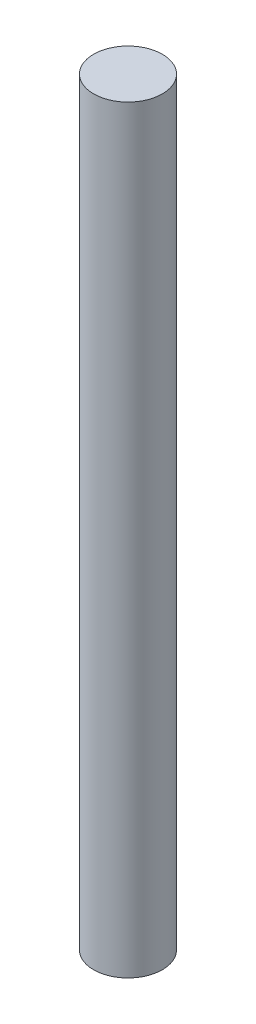
SolidWorks part; units mm, degrees
ref_plane "Front Plane" through (0, 0, 0) normal (0, 0, 1) x (1, 0, 0)
ref_plane "Top Plane" through (0, 0, 0) normal (0, 1, 0) x (1, 0, 0)
ref_plane "Right Plane" through (0, 0, 0) normal (1, 0, 0) x (0, 0, -1)
sketch "Sketch1" plane through (0, 0, 0) normal (0, 1, 0) x (1, 0, 0)
  circle A0 centre (0, 0) radius 6.477
  dimension "D1" = 12.954
extrude "Boss-Extrude1" add sketch "Sketch1" along normal blind 143.002
